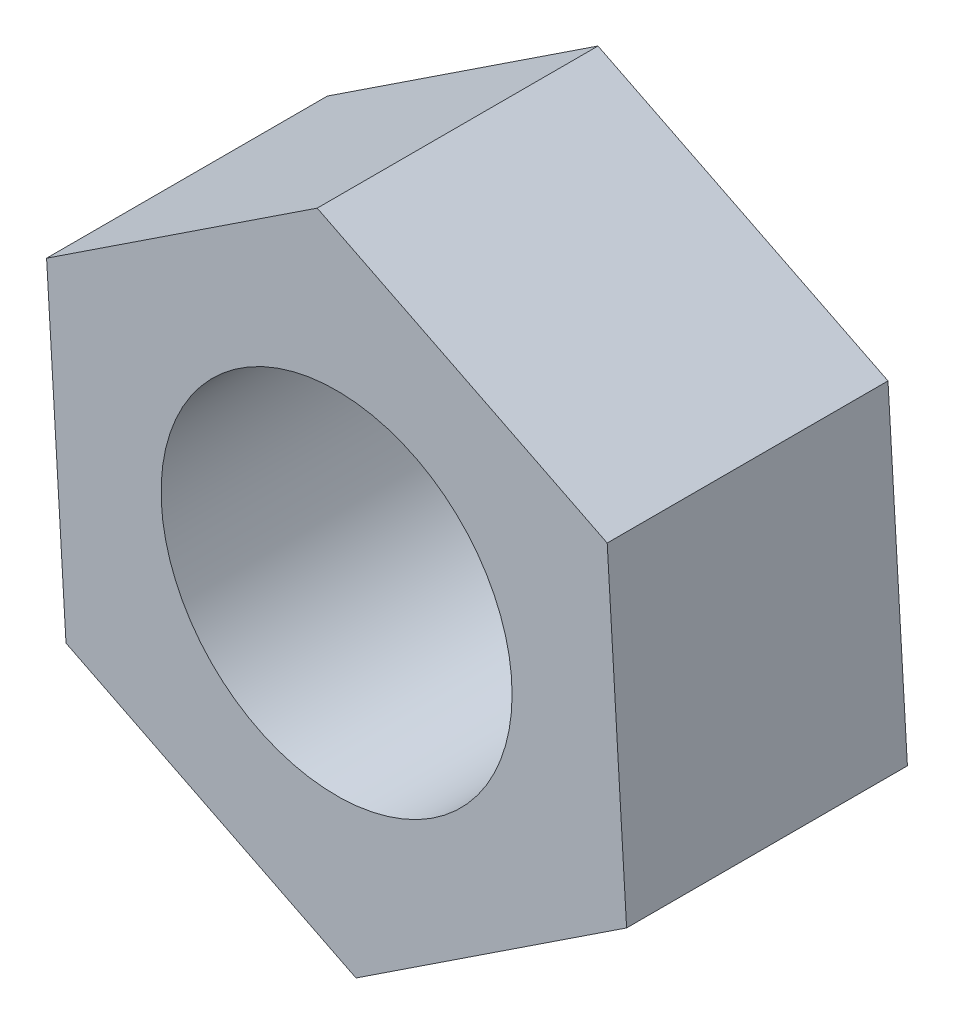
SolidWorks part; units mm, degrees
ref_plane "Front Plane" through (0, 0, 0) normal (0, 0, 1) x (1, 0, 0)
ref_plane "Top Plane" through (0, 0, 0) normal (0, 1, 0) x (1, 0, 0)
ref_plane "Right Plane" through (0, 0, 0) normal (1, 0, 0) x (0, 0, -1)
sketch "Sketch1" plane through (0, 0, 0) normal (0, 0, 1) x (1, 0, 0)
  line L1 (3.8546, 2.5447) -> (-0.2764, 4.6105)
  line L2 (-0.2764, 4.6105) -> (-4.1311, 2.0659)
  line L3 (-4.1311, 2.0659) -> (-3.8546, -2.5447)
  line L4 (-3.8546, -2.5447) -> (0.2764, -4.6105)
  line L5 (0.2764, -4.6105) -> (4.1311, -2.0659)
  line L6 (4.1311, -2.0659) -> (3.8546, 2.5447)
  circle A0 centre (0, 0) radius 4 construction
  dimension "D1" = 8
extrude "Boss-Extrude1" add sketch "Sketch1" along normal blind 4
sketch "Sketch2" plane through (0, 0, 4) normal (0, 0, 1) x (1, 0, 0)
  circle A0 centre (0, 0) radius 2.5
  dimension "D1" = 5
extrude "Cut-Extrude1" cut sketch "Sketch2" against normal blind 10
